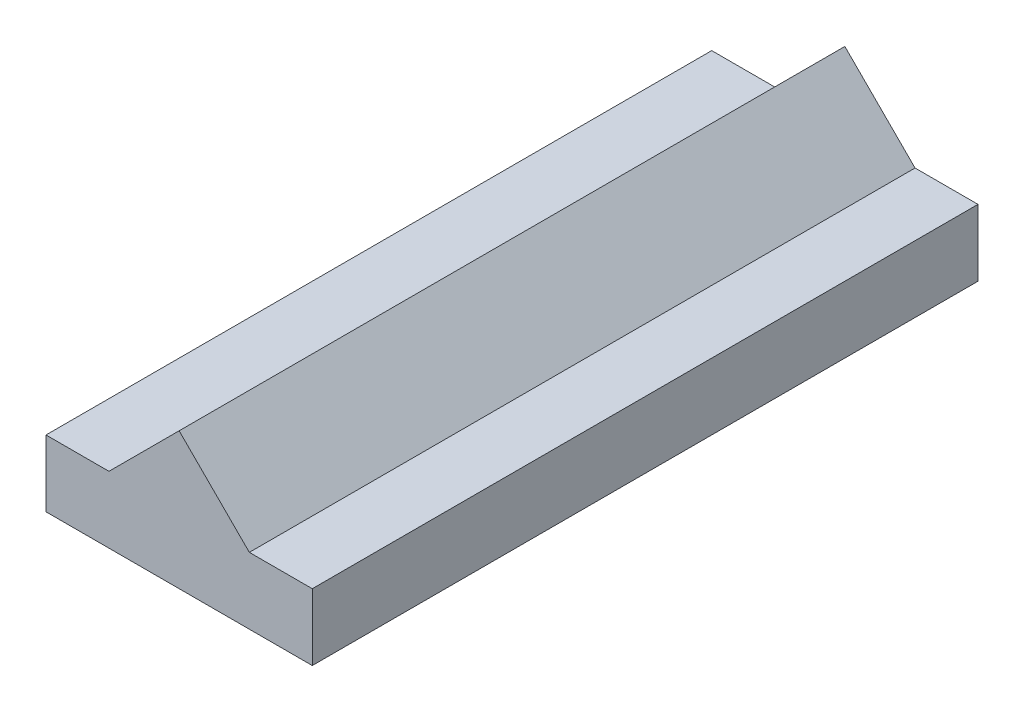
SolidWorks part; units mm, degrees
ref_plane "Front Plane" through (0, 0, 0) normal (0, 0, 1) x (1, 0, 0)
ref_plane "Top Plane" through (0, 0, 0) normal (0, 1, 0) x (1, 0, 0)
ref_plane "Right Plane" through (0, 0, 0) normal (1, 0, 0) x (0, 0, -1)
sketch "Sketch1" plane through (0, 0, 0) normal (0, 0, 1) x (1, 0, 0)
  line L1 (10, 0) -> (10, 5)
  line L2 (10, 5) -> (5.2718, 5)
  line L3 (5.2718, 5) -> (0, 10.2718)
  line L4 (0, 10.2718) -> (-5.2718, 5)
  line L5 (-5.2718, 5) -> (-10, 5)
  line L6 (-10, 5) -> (-10, 0)
  line L8 (-10, 0) -> (10, 0)
  point P1 (0, 0)
  point P3 (85.8847, 11.1916)
  point P10 (10, 25.4711)
  point P12 (-5.6901, 5)
  point P13 (-1.3187, 11.9921)
  point P14 (2.5874, 5.6888)
  point P15 (0, 0)
  dimension "D1" = 5
  dimension "D2" = 20
  dimension "D3" = 90
  dimension "D4" = 7.4554
extrude "Boss-Extrude1" add sketch "Sketch1" along normal blind 50
sketch "Orientation Sketch" plane through (0, 5, 0) normal (0, 1, 0) x (1, 0, 0)
  line L0 (-5.2718, 0) -> (-10, 0) construction
  line L1 (-10, -50) -> (-10, 0) construction
  line L2 (-5.2718, -50) -> (-10, -50) construction
  line L3 (-5.2718, -50) -> (-5.2718, 0) construction
  line L4 (-5.2718, 0) -> (-10, 0)
  line L5 (-10, -50) -> (-10, 0)
  line L6 (-5.2718, -50) -> (-10, -50)
  line L7 (-5.2718, -50) -> (-5.2718, 0)
  point P4 (-7.6359, -25)
other "FormTool1"
